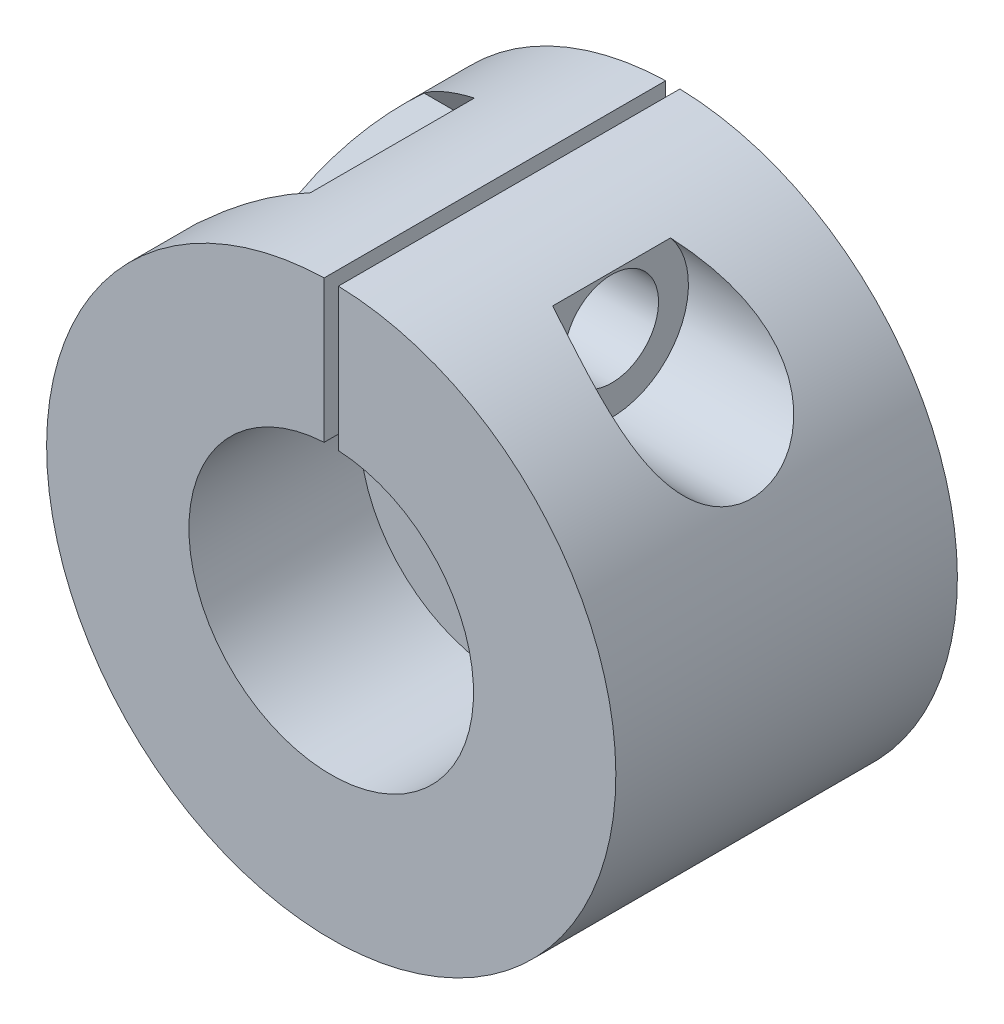
SolidWorks part; units mm, degrees
ref_plane "Front Plane" through (0, 0, 0) normal (0, 0, 1) x (1, 0, 0)
ref_plane "Top Plane" through (0, 0, 0) normal (0, 1, 0) x (1, 0, 0)
ref_plane "Right Plane" through (0, 0, 0) normal (1, 0, 0) x (0, 0, -1)
sketch "Sketch1" plane through (0, 0, 0) normal (0, 0, 1) x (1, 0, 0)
  circle A0 centre (0, 0) radius 12.7
  dimension "D1" = 25.4
extrude "Boss-Extrude1" add sketch "Sketch1" along normal blind 15.24
sketch "Sketch2" plane through (0, 0, 0) normal (0, 0, -1) x (-1, 0, 0)
  circle A0 centre (0, 0) radius 2.9845
  dimension "D1" = 5.969
extrude "Cut-Extrude1" cut sketch "Sketch2" against normal blind 7.62 contours A0
sketch "Sketch3" plane through (0, 0, 15.24) normal (0, 0, 1) x (1, 0, 0)
  circle A0 centre (0, 0) radius 6.35
  dimension "D1" = 12.7
extrude "Cut-Extrude2" cut sketch "Sketch3" against normal up to surface (7.62 mm away) contours A0 up to face at (-2.9845, 0, 7.62)
sketch "Sketch5" plane through (0, 0, 0) normal (0, 0, -1) x (-1, 0, 0)
  line L0 (0, 0) -> (0, 12.7) construction
  circle A0 centre (0, 0) radius 12.7 construction
  circle A1 centre (0, 0) radius 12.7 construction
  point P5 (8.077, 9.8007)
  point P6 (0, 0)
  point P8 (0, 12.7)
sketch "Sketch7" plane through (0, 0, 0) normal (0, 0, -1) x (-1, 0, 0)
  line L0 (0, 0) -> (0, 12.7) construction
  line L1 (-0.3175, -0.635) -> (0.3175, -0.635)
  line L2 (-0.3175, -0.635) -> (-0.3175, 13.335)
  line L3 (-0.3175, 13.335) -> (0.3175, 13.335)
  line L4 (0.3175, -0.635) -> (0.3175, 13.335)
  line L5 (-0.3175, -0.635) -> (0.3175, 13.335) construction
  line L6 (-0.3175, 13.335) -> (0.3175, -0.635) construction
  point P0 (0, 6.35)
  dimension "D1" = 13.97
  dimension "D2" = 0.635
extrude "Cut-Extrude3" cut sketch "Sketch7" against normal up to next
sketch "Sketch8" plane through (0.3175, 0, 0) normal (-1, 0, 0) x (0, 0, 1)
  line L0 (15.24, 12.696) -> (15.24, 6.3421) construction
  line L1 (15.24, 12.696) -> (0, 12.696) construction
  circle A0 centre (7.62, 9.521) radius 2.0955
  dimension "D1" = 4.191
  dimension "D2" = 7.62
  dimension "D3" = 3.175
extrude "Cut-Extrude4" cut sketch "Sketch8" against normal through all both and the other way through all
sketch3d "3DSketch2" plane through (0, 0, 0) normal (0, 0, 1) x (1, 0, 0)
  dimension "D1" = 4.572
sketch "Sketch9" plane through (4.8895, 0, 0) normal (-1, 0, 0) x (0, 0, 1)
  circle A0 centre (7.62, 9.521) radius 3.429
  dimension "D1" = 6.858
extrude "Cut-Extrude5" cut sketch "Sketch9" against normal blind 7.62 contours A0
sketch3d "3DSketch3" plane through (0, 0, 0) normal (0, 0, 1) x (1, 0, 0)
  dimension "D1" = 4.572
sketch "Sketch10" plane through (-4.8895, 0, 0) normal (1, 0, 0) x (0, 0, -1)
  line L0 (0, 12.696) -> (-15.24, 12.696) construction
  line L1 (-10.0837, 5.2538) -> (-5.1563, 5.2538)
  line L2 (-5.1563, 5.2538) -> (-2.6927, 9.521)
  line L3 (-2.6927, 9.521) -> (-5.1563, 13.7882)
  line L4 (-5.1563, 13.7882) -> (-10.0837, 13.7882)
  line L5 (-10.0837, 13.7882) -> (-12.5473, 9.521)
  line L6 (-12.5473, 9.521) -> (-10.0837, 5.2538)
  circle A0 centre (-7.62, 9.521) radius 4.2672 construction
  dimension "D1" = 8.5344
extrude "Cut-Extrude6" cut sketch "Sketch10" against normal through all contours L3 L4 L5 L6 L1 L2
